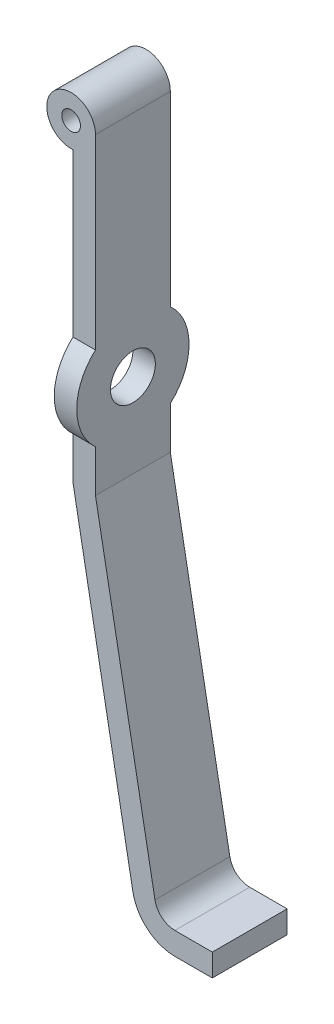
SolidWorks part; units mm, degrees
ref_plane "Front Plane" through (0, 0, 0) normal (0, 0, 1) x (1, 0, 0)
ref_plane "Top Plane" through (0, 0, 0) normal (0, 1, 0) x (1, 0, 0)
ref_plane "Right Plane" through (0, 0, 0) normal (1, 0, 0) x (0, 0, -1)
sketch "Sketch1" plane through (0, 0, 0) normal (0, 0, 1) x (1, 0, 0)
  line L0 (0.25, -3.2404) -> (0.25, -41.7404)
  line L2 (3.25, -41.7404) -> (3.25, 0)
  line L3 (13.8553, -86.7404) -> (18.8553, -86.7404)
  line L4 (18.8553, -86.7404) -> (18.8553, -89.7404)
  line L5 (18.8553, -89.7404) -> (13.8553, -89.7404)
  line L6 (0.25, -41.7404) -> (8.25, -85.0752)
  line L7 (3.25, -41.7404) -> (11.2007, -84.5336)
  circle A0 centre (0, 0) radius 1.25
  arc A1 (3.25, 0) -> (0.25, -3.2404) centre (0, 0) ccw
  arc A2 (8.25, -85.0752) -> (13.8553, -89.7404) centre (13.8553, -84.0404) ccw
  arc A3 (11.2007, -84.5336) -> (13.8553, -86.7404) centre (13.8553, -84.0404) ccw
  point P10 (20.8061, -86.8232)
  point P13 (0, 0)
  point P16 (3.25, -41.7404)
  dimension "D1" = 2.5
  dimension "D2" = 2
  dimension "D5" = 5.4
  dimension "D7" = 3
  dimension "D3" = 3
  dimension "D4" = 45
  dimension "D6" = 5
  dimension "D9" = 38.5
  dimension "D10" = 8
extrude "Boss-Extrude1" add sketch "Sketch1" along normal blind 10
sketch "Sketch2" plane through (0.25, 0, 0) normal (-1, 0, 0) x (0, 0, 1)
  line L1 (5, 0) -> (5, -30.5) construction
  line L4 (5, 0) -> (17.3739, 0) construction
  line L5 (10, -41.7404) -> (0, -41.7404) construction
  circle A0 centre (5, -30.5) radius 3
  point P4 (5, -41.7404)
  dimension "D2" = 6
  dimension "D1" = 30.5
extrude "Cut-Extrude1" cut sketch "Sketch2" against normal up to next
sketch "Sketch3" plane through (0.25, 0, 0) normal (-1, 0, 0) x (0, 0, 1)
  circle A0 centre (5, -30.5) radius 7.5
  circle A1 centre (5, -30.5) radius 3
  circle A2 centre (5, -30.5) radius 3 construction
  dimension "D1" = 15
extrude "Boss-Extrude2" add sketch "Sketch3" against normal up to surface (3 mm away) up to face at (3.25, -33.5, 5)
